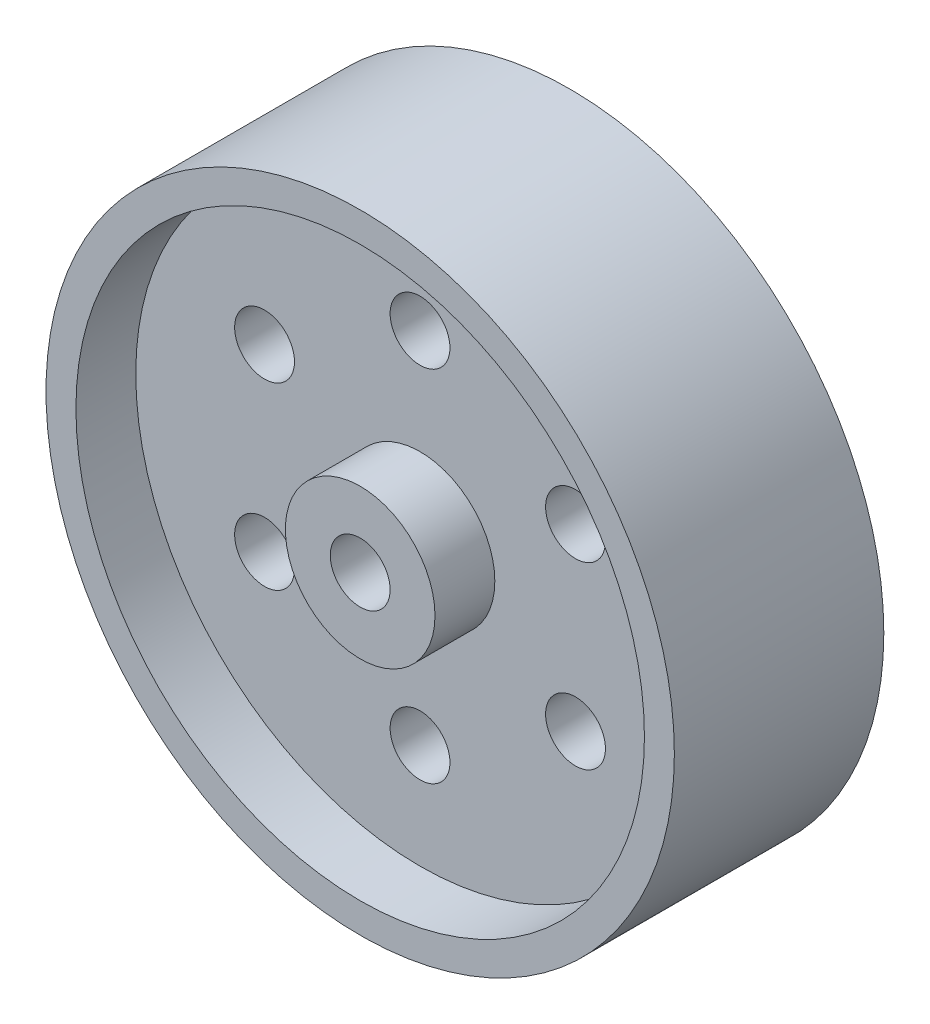
SolidWorks part; units mm, degrees
ref_plane "Front Plane" through (0, 0, 0) normal (0, 0, 1) x (1, 0, 0)
ref_plane "Top Plane" through (0, 0, 0) normal (0, 1, 0) x (1, 0, 0)
ref_plane "Right Plane" through (0, 0, 0) normal (1, 0, 0) x (0, 0, -1)
sketch "Sketch1" plane through (0, 0, 0) normal (1, 0, 0) x (0, 0, -1)
  line L0 (-26.8717, 0) -> (30.8018, 0) construction
  line L1 (-7, 2) -> (-7, 5)
  line L2 (-7, 5) -> (-3, 5)
  line L3 (-3, 5) -> (-3, 19)
  line L4 (-3, 19) -> (-7, 19)
  line L5 (-7, 19) -> (-7, 21)
  line L6 (-7, 21) -> (7, 21)
  line L7 (7, 21) -> (7, 15)
  line L8 (7, 15) -> (3, 15)
  line L10 (-7, 2) -> (3, 2)
  line L11 (0, 21) -> (0, 0) construction
  line L12 (3, 2) -> (3, 15)
  point P15 (-3, 12)
  dimension "D1" = 15
  dimension "D2" = 2
  dimension "D3" = 5
  dimension "D4" = 19
  dimension "D5" = 21
  dimension "D6" = 4
  dimension "D7" = 4
  dimension "D8" = 13
  dimension "D10" = 14
revolve "Revolve1" add sketch "Sketch1" angle 360 about L0
sketch "Sketch2" plane through (0, 0, 3) normal (0, 0, 1) x (1, 0, 0)
  line L0 (0, 5) -> (0, 19) construction
  circle A0 centre (0, 12) radius 2
  circle A5 centre (0, 0) radius 5 construction
  circle A6 centre (0, 0) radius 5 construction
  circle A7 centre (0, 0) radius 19 construction
  circle A8 centre (10.3923, 6) radius 2
  circle A9 centre (10.3923, -6) radius 2
  circle A10 centre (0, -12) radius 2
  circle A11 centre (-10.3923, -6) radius 2
  circle A12 centre (-10.3923, 6) radius 2
  point P26 (0, 0)
  dimension "D1" = 4
  dimension "D2" = 6
extrude "Cut-Extrude1" cut sketch "Sketch2" against normal through all both and the other way through all
